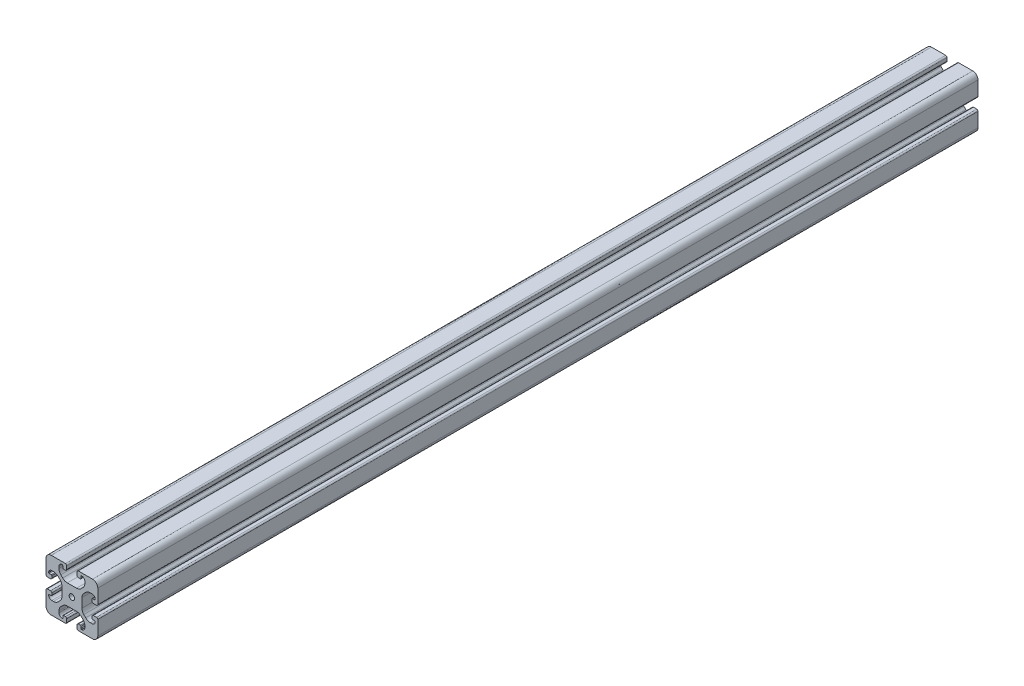
SolidWorks part; units mm, degrees
material "氧化铝"
ref_plane "前视基准面" through (0, 0, 0) normal (0, 0, 1) x (1, 0, 0)
ref_plane "上视基准面" through (0, 0, 0) normal (0, 1, 0) x (1, 0, 0)
ref_plane "右视基准面" through (0, 0, 0) normal (1, 0, 0) x (0, 0, -1)
sketch "Model" plane through (0, 0, 0) normal (0, 0, 1) x (1, 0, 0)
  line L2 (3038.626, 1538.5549) -> (3045.7412, 1538.5549)
  line L3 (3037.1836, 1526.3047) -> (3026.1835, 1526.3048)
  line L4 (3032.1835, 1530.8048) -> (3032.1835, 1532.1123)
  line L5 (3033.6481, 1535.6478) -> (3035.0903, 1537.0902)
  line L6 (3034.7336, 1528.3048) -> (3034.6836, 1528.3048)
  line L7 (3037.1836, 1530.8048) -> (3035.6835, 1530.8048)
  line L8 (3035.1835, 1528.7549) -> (3035.1835, 1530.3049)
  line L9 (3022.1835, 1530.305) -> (3022.1835, 1541.3049)
  line L10 (3038.1835, 1565.3049) -> (3038.1835, 1562.8049)
  line L11 (3031.5267, 1554.8404) -> (3032.9691, 1553.398)
  line L12 (3026.6837, 1556.305) -> (3027.9911, 1556.305)
  line L13 (3026.1835, 1553.305) -> (3024.6335, 1553.305)
  line L14 (3024.1836, 1553.7549) -> (3024.1836, 1553.8049)
  line L15 (3026.6837, 1551.3049) -> (3026.6837, 1552.805)
  line L16 (3023.1837, 1550.305) -> (3025.6835, 1550.305)
  line L17 (3022.1835, 1562.3048) -> (3022.1835, 1551.3049)
  line L18 (3023.1837, 1542.3048) -> (3025.6835, 1542.3048)
  line L19 (3026.6837, 1541.3049) -> (3026.6837, 1539.8048)
  line L20 (3024.1836, 1538.8549) -> (3024.1836, 1538.8048)
  line L21 (3026.1835, 1539.3048) -> (3024.6335, 1539.3048)
  line L22 (3026.6837, 1536.3048) -> (3027.9911, 1536.3048)
  line L23 (3031.5267, 1537.7694) -> (3032.9691, 1539.2118)
  line L24 (3035.1835, 1563.8549) -> (3035.1835, 1562.3049)
  line L25 (3037.1836, 1561.805) -> (3035.6835, 1561.805)
  line L26 (3034.7336, 1564.305) -> (3034.6836, 1564.305)
  line L27 (3038.1835, 1527.3048) -> (3038.1835, 1529.8049)
  line L28 (3049.9338, 1549.8624) -> (3049.9338, 1542.7473)
  line L29 (3047.1836, 1566.3051) -> (3058.1838, 1566.305)
  line L30 (3052.1837, 1561.805) -> (3052.1837, 1560.4975)
  line L31 (3050.7191, 1556.962) -> (3049.2769, 1555.5195)
  line L32 (3033.6481, 1556.962) -> (3035.0903, 1555.5195)
  line L33 (3032.1835, 1561.805) -> (3032.1835, 1560.4975)
  line L34 (3046.1837, 1527.3048) -> (3046.1837, 1529.8049)
  line L35 (3049.6336, 1564.305) -> (3049.6837, 1564.305)
  line L36 (3047.1836, 1561.805) -> (3048.6837, 1561.805)
  line L37 (3049.1837, 1563.8549) -> (3049.1837, 1562.3049)
  line L38 (3052.8406, 1537.7694) -> (3051.3981, 1539.2118)
  line L39 (3057.6836, 1536.3048) -> (3056.3761, 1536.3048)
  line L40 (3058.1838, 1539.3048) -> (3059.7337, 1539.3048)
  line L41 (3060.1836, 1538.8549) -> (3060.1836, 1538.8048)
  line L42 (3057.6836, 1541.3049) -> (3057.6836, 1539.8048)
  line L43 (3061.1835, 1542.3048) -> (3058.6837, 1542.3048)
  line L44 (3037.1836, 1566.3051) -> (3026.1835, 1566.305)
  line L45 (3062.1837, 1562.3048) -> (3062.1837, 1551.3049)
  line L46 (3038.626, 1554.0549) -> (3045.7412, 1554.0549)
  line L47 (3061.1835, 1550.305) -> (3058.6837, 1550.305)
  line L48 (3057.6836, 1551.3049) -> (3057.6836, 1552.805)
  line L49 (3060.1836, 1553.7549) -> (3060.1836, 1553.8049)
  line L50 (3058.1838, 1553.305) -> (3059.7337, 1553.305)
  line L51 (3057.6836, 1556.305) -> (3056.3761, 1556.305)
  line L52 (3034.4335, 1549.8624) -> (3034.4335, 1542.7473)
  line L53 (3052.8406, 1554.8404) -> (3051.3981, 1553.398)
  line L54 (3046.1837, 1565.3049) -> (3046.1837, 1562.8049)
  line L55 (3062.1837, 1530.305) -> (3062.1837, 1541.3049)
  line L56 (3049.1837, 1528.7549) -> (3049.1837, 1530.3049)
  line L57 (3047.1836, 1530.8048) -> (3048.6837, 1530.8048)
  line L58 (3049.6336, 1528.3048) -> (3049.6837, 1528.3048)
  line L59 (3050.7191, 1535.6478) -> (3049.2769, 1537.0902)
  line L60 (3052.1837, 1530.8048) -> (3052.1837, 1532.1123)
  line L61 (3047.1836, 1526.3047) -> (3058.1838, 1526.3048)
  spline S0 degree 3 poles (3026.1835, 1526.3048) (3024.8345, 1526.3048) (3023.0907, 1527.3653) (3022.1835, 1529.3623) (3022.1835, 1530.305) knots 0 0 0 0 0.550544 1 1 1 1
  spline S1 degree 3 poles (3032.1835, 1532.1123) (3032.1835, 1532.8016) (3032.4749, 1534.0839) (3033.1746, 1535.1743) (3033.6481, 1535.6478) knots 0 0 0 0 0.510204 1 1 1 1
  spline S2 degree 3 poles (3035.0903, 1537.0902) (3035.5565, 1537.5565) (3036.6626, 1538.2661) (3037.9261, 1538.5549) (3038.626, 1538.5549) knots 0 0 0 0 0.489373 1 1 1 1
  spline S3 degree 3 poles (3038.1835, 1529.8049) (3038.1835, 1530.1088) (3037.8896, 1530.5989) (3037.4374, 1530.8048) (3037.1836, 1530.8048) knots 0 0 0 0 0.565195 1 1 1 1
  spline S4 degree 3 poles (3035.6835, 1530.8048) (3035.5526, 1530.8048) (3035.3033, 1530.6873) (3035.1835, 1530.4632) (3035.1835, 1530.3049) knots 0 0 0 0 0.482406 1 1 1 1
  spline S5 degree 3 poles (3035.1835, 1528.7549) (3035.1835, 1528.6211) (3035.0566, 1528.3999) (3034.8531, 1528.3048) (3034.7336, 1528.3048) knots 0 0 0 0 0.549542 1 1 1 1
  spline S6 degree 3 poles (3034.6836, 1528.3048) (3033.9863, 1528.3048) (3032.7434, 1528.9085) (3032.1835, 1530.0457) (3032.1835, 1530.8048) knots 0 0 0 0 0.502794 1 1 1 1
  spline S7 degree 3 poles (3022.1835, 1541.3049) (3022.1835, 1541.6421) (3022.4486, 1542.0781) (3022.9479, 1542.3048) (3023.1837, 1542.3048) knots 0 0 0 0 0.550415 1 1 1 1
  spline S8 degree 3 poles (3025.6835, 1542.3048) (3026.0194, 1542.3048) (3026.4561, 1542.0413) (3026.6837, 1541.5421) (3026.6837, 1541.3049) knots 0 0 0 0 0.548464 1 1 1 1
  spline S9 degree 3 poles (3026.6837, 1539.8048) (3026.6837, 1539.6386) (3026.5536, 1539.4195) (3026.3039, 1539.3048) (3026.1835, 1539.3048) knots 0 0 0 0 0.543008 1 1 1 1
  spline S10 degree 3 poles (3024.6335, 1539.3048) (3024.4666, 1539.3048) (3024.2778, 1539.1702) (3024.1836, 1538.9461) (3024.1836, 1538.8549) knots 0 0 0 0 0.601272 1 1 1 1
  spline S11 degree 3 poles (3024.1836, 1538.8048) (3024.1836, 1537.973) (3024.8335, 1536.8769) (3026.0817, 1536.3048) (3026.6837, 1536.3048) knots 0 0 0 0 0.543506 1 1 1 1
  spline S12 degree 3 poles (3027.9911, 1536.3048) (3028.6698, 1536.3048) (3029.9377, 1536.5775) (3031.0429, 1537.2857) (3031.5267, 1537.7694) knots 0 0 0 0 0.495307 1 1 1 1
  spline S13 degree 3 poles (3032.9691, 1539.2118) (3033.4334, 1539.6761) (3034.1274, 1540.7681) (3034.4335, 1542.0508) (3034.4335, 1542.7473) knots 0 0 0 0 0.481772 1 1 1 1
  spline S14 degree 3 poles (3037.1836, 1526.3047) (3037.4, 1526.3047) (3037.8987, 1526.5226) (3038.1835, 1526.9491) (3038.1835, 1527.3048) knots 0 0 0 0 0.421049 1 1 1 1
  spline S15 degree 3 poles (3058.1838, 1566.305) (3059.5327, 1566.305) (3061.2765, 1565.2445) (3062.1837, 1563.2474) (3062.1837, 1562.3048) knots 0 0 0 0 0.550544 1 1 1 1
  spline S16 degree 3 poles (3052.1837, 1560.4975) (3052.1837, 1559.8082) (3051.8923, 1558.5259) (3051.1926, 1557.4355) (3050.7191, 1556.962) knots 0 0 0 0 0.510204 1 1 1 1
  spline S17 degree 3 poles (3049.2769, 1555.5195) (3048.8108, 1555.0533) (3047.7046, 1554.3437) (3046.4411, 1554.0549) (3045.7412, 1554.0549) knots 0 0 0 0 0.489373 1 1 1 1
  spline S18 degree 3 poles (3046.1837, 1562.8049) (3046.1837, 1562.501) (3046.4776, 1562.0109) (3046.9298, 1561.805) (3047.1836, 1561.805) knots 0 0 0 0 0.565195 1 1 1 1
  spline S19 degree 3 poles (3037.1836, 1566.3051) (3037.4, 1566.3051) (3037.8987, 1566.0872) (3038.1835, 1565.6607) (3038.1835, 1565.3049) knots 0 0 0 0 0.421049 1 1 1 1
  spline S20 degree 3 poles (3048.6837, 1561.805) (3048.8146, 1561.805) (3049.0639, 1561.9225) (3049.1837, 1562.1466) (3049.1837, 1562.3049) knots 0 0 0 0 0.482406 1 1 1 1
  spline S21 degree 3 poles (3032.9691, 1553.398) (3033.4334, 1552.9336) (3034.1274, 1551.8416) (3034.4335, 1550.559) (3034.4335, 1549.8624) knots 0 0 0 0 0.481772 1 1 1 1
  spline S22 degree 3 poles (3027.9911, 1556.305) (3028.6698, 1556.305) (3029.9377, 1556.0322) (3031.0429, 1555.3241) (3031.5267, 1554.8404) knots 0 0 0 0 0.495307 1 1 1 1
  spline S23 degree 3 poles (3024.1836, 1553.8049) (3024.1836, 1554.6368) (3024.8335, 1555.7328) (3026.0817, 1556.305) (3026.6837, 1556.305) knots 0 0 0 0 0.543506 1 1 1 1
  spline S24 degree 3 poles (3024.6335, 1553.305) (3024.4666, 1553.305) (3024.2778, 1553.4396) (3024.1836, 1553.6637) (3024.1836, 1553.7549) knots 0 0 0 0 0.601272 1 1 1 1
  spline S25 degree 3 poles (3026.6837, 1552.805) (3026.6837, 1552.9712) (3026.5536, 1553.1903) (3026.3039, 1553.305) (3026.1835, 1553.305) knots 0 0 0 0 0.543008 1 1 1 1
  spline S26 degree 3 poles (3025.6835, 1550.305) (3026.0194, 1550.305) (3026.4561, 1550.5685) (3026.6837, 1551.0677) (3026.6837, 1551.3049) knots 0 0 0 0 0.548464 1 1 1 1
  spline S27 degree 3 poles (3022.1835, 1551.3049) (3022.1835, 1550.9677) (3022.4486, 1550.5317) (3022.9479, 1550.305) (3023.1837, 1550.305) knots 0 0 0 0 0.550415 1 1 1 1
  spline S28 degree 3 poles (3049.1837, 1563.8549) (3049.1837, 1563.9886) (3049.3106, 1564.2099) (3049.5141, 1564.305) (3049.6336, 1564.305) knots 0 0 0 0 0.549542 1 1 1 1
  spline S29 degree 3 poles (3049.6837, 1564.305) (3050.3809, 1564.305) (3051.6238, 1563.7012) (3052.1837, 1562.5641) (3052.1837, 1561.805) knots 0 0 0 0 0.502794 1 1 1 1
  spline S30 degree 3 poles (3062.1837, 1551.3049) (3062.1837, 1550.9677) (3061.9186, 1550.5317) (3061.4193, 1550.305) (3061.1835, 1550.305) knots 0 0 0 0 0.550415 1 1 1 1
  spline S31 degree 3 poles (3058.6837, 1550.305) (3058.3478, 1550.305) (3057.9111, 1550.5685) (3057.6836, 1551.0677) (3057.6836, 1551.3049) knots 0 0 0 0 0.548464 1 1 1 1
  spline S32 degree 3 poles (3057.6836, 1552.805) (3057.6836, 1552.9712) (3057.8136, 1553.1903) (3058.0633, 1553.305) (3058.1838, 1553.305) knots 0 0 0 0 0.543008 1 1 1 1
  spline S33 degree 3 poles (3059.7337, 1553.305) (3059.9006, 1553.305) (3060.0894, 1553.4396) (3060.1836, 1553.6637) (3060.1836, 1553.7549) knots 0 0 0 0 0.601272 1 1 1 1
  spline S34 degree 3 poles (3060.1836, 1553.8049) (3060.1836, 1554.6368) (3059.5337, 1555.7328) (3058.2856, 1556.305) (3057.6836, 1556.305) knots 0 0 0 0 0.543506 1 1 1 1
  spline S35 degree 3 poles (3056.3761, 1556.305) (3055.6974, 1556.305) (3054.4295, 1556.0322) (3053.3243, 1555.3241) (3052.8406, 1554.8404) knots 0 0 0 0 0.495307 1 1 1 1
  spline S36 degree 3 poles (3051.3981, 1553.398) (3050.9338, 1552.9336) (3050.2398, 1551.8416) (3049.9338, 1550.559) (3049.9338, 1549.8624) knots 0 0 0 0 0.481772 1 1 1 1
  spline S37 degree 3 poles (3047.1836, 1566.3051) (3046.9672, 1566.3051) (3046.4685, 1566.0872) (3046.1837, 1565.6607) (3046.1837, 1565.3049) knots 0 0 0 0 0.421049 1 1 1 1
  spline S38 degree 3 poles (3034.6836, 1564.305) (3033.9863, 1564.305) (3032.7434, 1563.7012) (3032.1835, 1562.5641) (3032.1835, 1561.805) knots 0 0 0 0 0.502794 1 1 1 1
  spline S39 degree 3 poles (3035.1835, 1563.8549) (3035.1835, 1563.9886) (3035.0566, 1564.2099) (3034.8531, 1564.305) (3034.7336, 1564.305) knots 0 0 0 0 0.549542 1 1 1 1
  spline S40 degree 3 poles (3035.6835, 1561.805) (3035.5526, 1561.805) (3035.3033, 1561.9225) (3035.1835, 1562.1466) (3035.1835, 1562.3049) knots 0 0 0 0 0.482406 1 1 1 1
  spline S41 degree 3 poles (3038.1835, 1562.8049) (3038.1835, 1562.501) (3037.8896, 1562.0109) (3037.4374, 1561.805) (3037.1836, 1561.805) knots 0 0 0 0 0.565195 1 1 1 1
  spline S42 degree 3 poles (3047.1836, 1526.3047) (3046.9672, 1526.3047) (3046.4685, 1526.5226) (3046.1837, 1526.9491) (3046.1837, 1527.3048) knots 0 0 0 0 0.421049 1 1 1 1
  spline S43 degree 3 poles (3051.3981, 1539.2118) (3050.9338, 1539.6761) (3050.2398, 1540.7681) (3049.9338, 1542.0508) (3049.9338, 1542.7473) knots 0 0 0 0 0.481772 1 1 1 1
  spline S44 degree 3 poles (3056.3761, 1536.3048) (3055.6974, 1536.3048) (3054.4295, 1536.5775) (3053.3243, 1537.2857) (3052.8406, 1537.7694) knots 0 0 0 0 0.495307 1 1 1 1
  spline S45 degree 3 poles (3060.1836, 1538.8048) (3060.1836, 1537.973) (3059.5337, 1536.8769) (3058.2856, 1536.3048) (3057.6836, 1536.3048) knots 0 0 0 0 0.543506 1 1 1 1
  spline S46 degree 3 poles (3059.7337, 1539.3048) (3059.9006, 1539.3048) (3060.0894, 1539.1702) (3060.1836, 1538.9461) (3060.1836, 1538.8549) knots 0 0 0 0 0.601272 1 1 1 1
  spline S47 degree 3 poles (3057.6836, 1539.8048) (3057.6836, 1539.6386) (3057.8136, 1539.4195) (3058.0633, 1539.3048) (3058.1838, 1539.3048) knots 0 0 0 0 0.543008 1 1 1 1
  spline S48 degree 3 poles (3058.6837, 1542.3048) (3058.3478, 1542.3048) (3057.9111, 1542.0413) (3057.6836, 1541.5421) (3057.6836, 1541.3049) knots 0 0 0 0 0.548464 1 1 1 1
  spline S49 degree 3 poles (3062.1837, 1541.3049) (3062.1837, 1541.6421) (3061.9186, 1542.0781) (3061.4193, 1542.3048) (3061.1835, 1542.3048) knots 0 0 0 0 0.550415 1 1 1 1
  spline S50 degree 3 poles (3049.6837, 1528.3048) (3050.3809, 1528.3048) (3051.6238, 1528.9085) (3052.1837, 1530.0457) (3052.1837, 1530.8048) knots 0 0 0 0 0.502794 1 1 1 1
  spline S51 degree 3 poles (3035.0903, 1555.5195) (3035.5565, 1555.0533) (3036.6626, 1554.3437) (3037.9261, 1554.0549) (3038.626, 1554.0549) knots 0 0 0 0 0.489373 1 1 1 1
  spline S52 degree 3 poles (3032.1835, 1560.4975) (3032.1835, 1559.8082) (3032.4749, 1558.5259) (3033.1746, 1557.4355) (3033.6481, 1556.962) knots 0 0 0 0 0.510204 1 1 1 1
  spline S53 degree 3 poles (3049.1837, 1528.7549) (3049.1837, 1528.6211) (3049.3106, 1528.3999) (3049.5141, 1528.3048) (3049.6336, 1528.3048) knots 0 0 0 0 0.549542 1 1 1 1
  spline S54 degree 3 poles (3048.6837, 1530.8048) (3048.8146, 1530.8048) (3049.0639, 1530.6873) (3049.1837, 1530.4632) (3049.1837, 1530.3049) knots 0 0 0 0 0.482406 1 1 1 1
  spline S55 degree 3 poles (3046.1837, 1529.8049) (3046.1837, 1530.1088) (3046.4776, 1530.5989) (3046.9298, 1530.8048) (3047.1836, 1530.8048) knots 0 0 0 0 0.565195 1 1 1 1
  spline S56 degree 3 poles (3049.2769, 1537.0902) (3048.8108, 1537.5565) (3047.7046, 1538.2661) (3046.4411, 1538.5549) (3045.7412, 1538.5549) knots 0 0 0 0 0.489373 1 1 1 1
  spline S57 degree 3 poles (3052.1837, 1532.1123) (3052.1837, 1532.8016) (3051.8923, 1534.0839) (3051.1926, 1535.1743) (3050.7191, 1535.6478) knots 0 0 0 0 0.510204 1 1 1 1
  spline S58 degree 3 poles (3058.1838, 1526.3048) (3059.5327, 1526.3048) (3061.2765, 1527.3653) (3062.1837, 1529.3623) (3062.1837, 1530.305) knots 0 0 0 0 0.550544 1 1 1 1
  spline S68 degree 3 poles (3026.1835, 1566.305) (3024.8345, 1566.305) (3023.0907, 1565.2445) (3022.1835, 1563.2474) (3022.1835, 1562.3048) knots 0 0 0 0 0.550544 1 1 1 1
extrude "凸台-拉伸3" add sketch "Model" along normal blind 680 contours S22 L11 S21 L52 S13 L23 S12 L22 S11 L20 S10 L21 S9 L19 S8 L18 S7 L9 S0 L3 S14 L27 S3 L7 S4 L8 S5 L6 S6 L4 S1 L5 S2 L2 S56 L59 S57 L60 S50 L58 S53 L56 S54 L57 S55 L34 S42 L61 S58 L55 S49 L43 S48 L42 S47 L40 S46 L41 S45 L39 S44 L38 S43 L28 S36 L53 S35 L51 S34 L49 S33 L50 S32 L48 S31 L47 S30 L45 S15 L29 S37 L54 S18 L36 S20 L37 S28 L35 S29 L30 S16 L31 S17 L46 S51 L32 S52 L33 S38 L26 S39 L24 S40 L25 S41 L10 S19 L44 S68 L17 S27 L16 S26 L15 S25 L13 S24 L14 S23 L12
sketch "草图1" plane through (0, 0, 680) normal (0, 0, 1) x (1, 0, 0)
  point P0 (3042.1836, 1546.3049)
hole_wizard "M5 螺纹孔1" positions "草图2" profile "草图3" tap size "M5" standard "GB" end condition through all
sketch "草图2" plane through (0, 0, 680) normal (0, 0, 1) x (1, 0, 0)
  point P0 (3042.1836, 1546.3049)
sketch "草图3" plane through (3042.1836, 1546.3049, 680) normal (1, 0, 0) x (0, -1, 0)
  line L0 (0, 0) -> (0, 680)
  line L1 (0, 680) -> (2.1, 680)
  line L2 (2.1, 680) -> (2.1, 0)
  line L5 (2.1, 0) -> (0, 0)
  line L11 (0, -6.35) -> (0, 107.95) construction
  dimension "通孔螺纹孔钻头直径" = 4.2
  dimension "通孔螺纹孔钻头深度" = 680
cosmetic thread "孔螺蚊线1" parameters "D2"=5
sketch "草图4" plane through (3049.9338, 0, 0) normal (1, 0, 0) x (0, 0, -1)
  line L0 (-680, 1549.8624) -> (-680, 1542.7473) construction
  point P0 (-340, 1546.3049)
  dimension "D1" = 340
hole_wizard "M5 螺纹孔2" positions "草图5" profile "草图6" tap size "M5" standard "GB" end condition through all
sketch "草图5" plane through (3049.9338, 0, 0) normal (1, 0, 0) x (0, 0, -1)
  point P0 (-340, 1546.3049)
sketch "草图6" plane through (3049.9338, 1546.3049, 340) normal (0, 1, 0) x (0, 0, -1)
  line L0 (0, 0) -> (0, 27.7503)
  line L1 (0, 27.7503) -> (2.1, 27.7503)
  line L2 (2.1, 27.7503) -> (2.1, 0)
  line L5 (2.1, 0) -> (0, 0)
  line L11 (0, -6.35) -> (0, 107.95) construction
  dimension "通孔螺纹孔钻头直径" = 4.2
  dimension "通孔螺纹孔钻头深度" = 27.7503
cosmetic thread "孔螺蚊线2" parameters "D2"=5
sketch "草图7" plane through (0, 1554.0549, 0) normal (0, 1, 0) x (1, 0, 0)
  line L0 (3038.626, 0) -> (3045.7412, 0) construction
  point P0 (3042.1836, -340)
  dimension "D1" = 340
hole_wizard "M5 螺纹孔3" positions "草图8" profile "草图9" tap size "M5" standard "GB" end condition through all
sketch "草图8" plane through (0, 1554.0549, 0) normal (0, 1, 0) x (1, 0, 0)
  point P0 (3042.1836, -340)
sketch "草图9" plane through (3042.1836, 1554.0549, 340) normal (1, 0, 0) x (0, 0, 1)
  line L0 (0, 0) -> (0, 27.7503)
  line L1 (0, 27.7503) -> (2.1, 27.7503)
  line L2 (2.1, 27.7503) -> (2.1, 0)
  line L5 (2.1, 0) -> (0, 0)
  line L11 (0, -6.35) -> (0, 107.95) construction
  dimension "通孔螺纹孔钻头直径" = 4.2
  dimension "通孔螺纹孔钻头深度" = 27.7503
cosmetic thread "孔螺蚊线3" parameters "D2"=5
